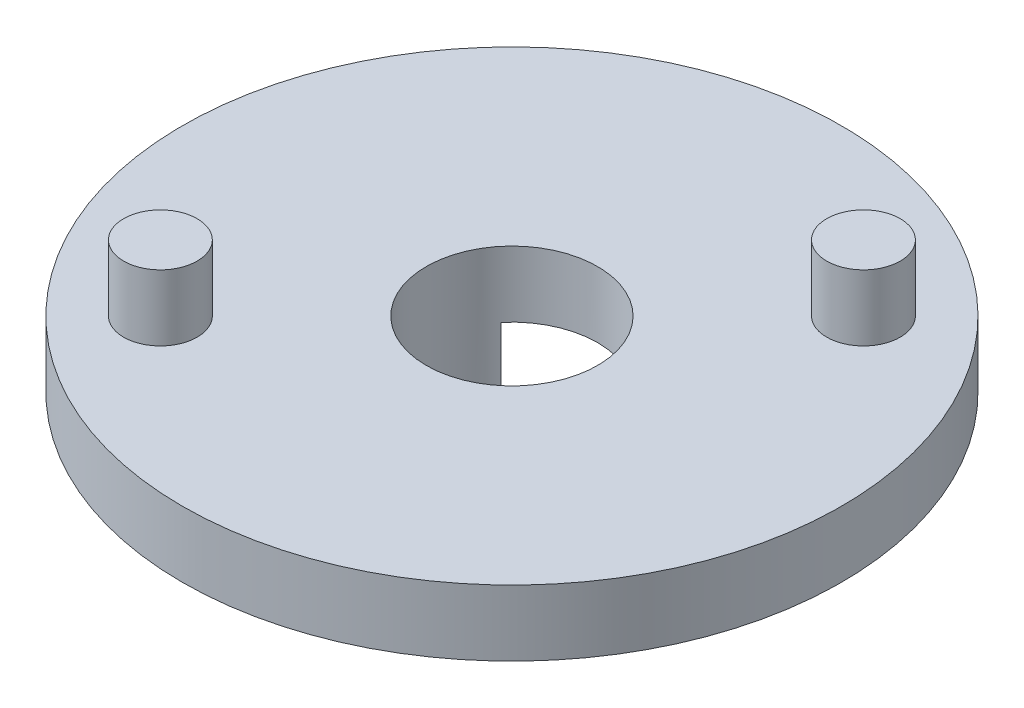
SolidWorks part; units mm, degrees
ref_plane "Front Plane" through (0, 0, 0) normal (0, 0, 1) x (1, 0, 0)
ref_plane "Top Plane" through (0, 0, 0) normal (0, 1, 0) x (1, 0, 0)
ref_plane "Right Plane" through (0, 0, 0) normal (1, 0, 0) x (0, 0, -1)
sketch "Sketch1" plane through (0, 0, 0) normal (0, 1, 0) x (1, 0, 0)
  line L5 (-2.6168, 1.25) -> (2.6168, 1.25)
  line L7 (-2.6168, -1.25) -> (2.6168, -1.25)
  line L9 (-2.6168, 1.25) -> (2.6168, -1.25) construction
  line L10 (-2.6168, -1.25) -> (2.6168, 1.25) construction
  arc A0 (-2.6168, 1.25) -> (-2.6168, -1.25) centre (0, 0) ccw
  arc A1 (2.6168, -1.25) -> (2.6168, 1.25) centre (0, 0) ccw
  point P0 (0, 0)
  dimension "D3" = 5.8
  dimension "D1" = 2.5
extrude "Boss-Extrude1" add sketch "Sketch1" along normal blind 1.75 contours L7 A1 L5 A0
sketch "Sketch2" plane through (0, 1.75, 0) normal (0, 1, 0) x (1, 0, 0)
  circle A0 centre (0, 0) radius 7.5
  dimension "D1" = 15
extrude "Boss-Extrude2" add sketch "Sketch2" along normal blind 1.5
sketch "Sketch3" plane through (0, 3.25, 0) normal (0, 1, 0) x (1, 0, 0)
  circle A0 centre (0, 0) radius 1.95
  dimension "D1" = 3.9
extrude "Cut-Extrude1" cut sketch "Sketch3" against normal through all
sketch "Sketch4" plane through (0, 3.25, 0) normal (0, 1, 0) x (1, 0, 0)
  line L0 (0, -55) -> (0, 55) construction
  circle A0 centre (4, 4) radius 0.8365
  circle A1 centre (-4, -4) radius 0.8365
  dimension "D1" = 1.673
  dimension "D2" = 4
  dimension "D3" = 4
  dimension "D4" = 1.673
  dimension "D5" = 4
  dimension "D6" = 4
extrude "Boss-Extrude3" add sketch "Sketch4" along normal blind 1.5
